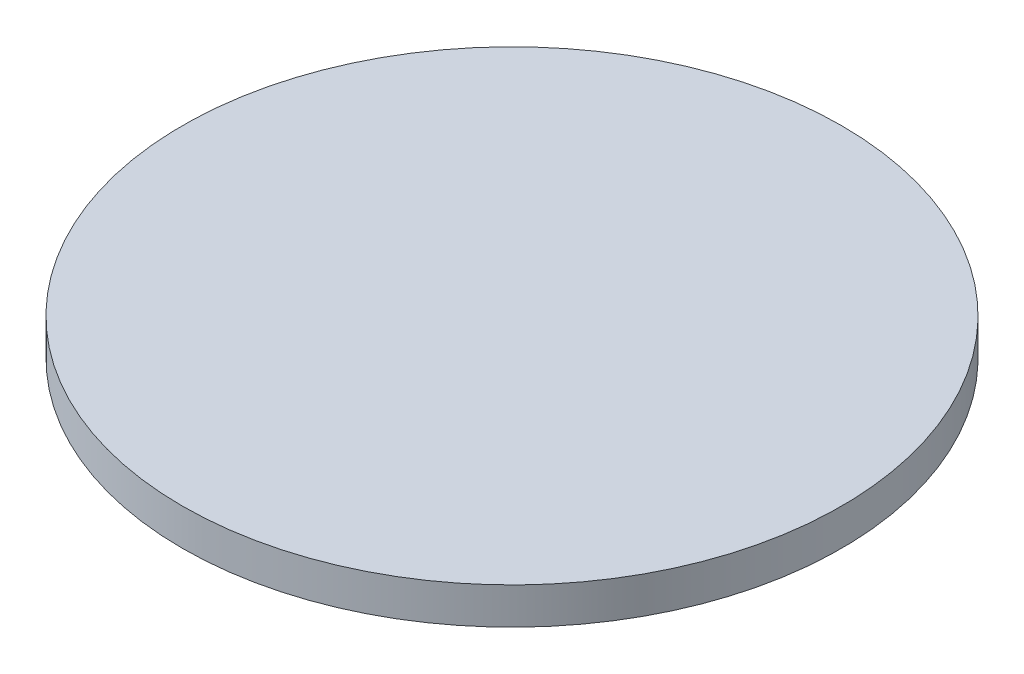
SolidWorks part; units mm, degrees
ref_plane "Front Plane" through (0, 0, 0) normal (0, 0, 1) x (1, 0, 0)
ref_plane "Top Plane" through (0, 0, 0) normal (0, 1, 0) x (1, 0, 0)
ref_plane "Right Plane" through (0, 0, 0) normal (1, 0, 0) x (0, 0, -1)
sketch "Sketch1" plane through (0, 0, 0) normal (0, 1, 0) x (1, 0, 0)
  circle A0 centre (0, 0) radius 114.3
  dimension "D1" = 228.6
extrude "Boss-Extrude1" add sketch "Sketch1" along normal blind 12.7
